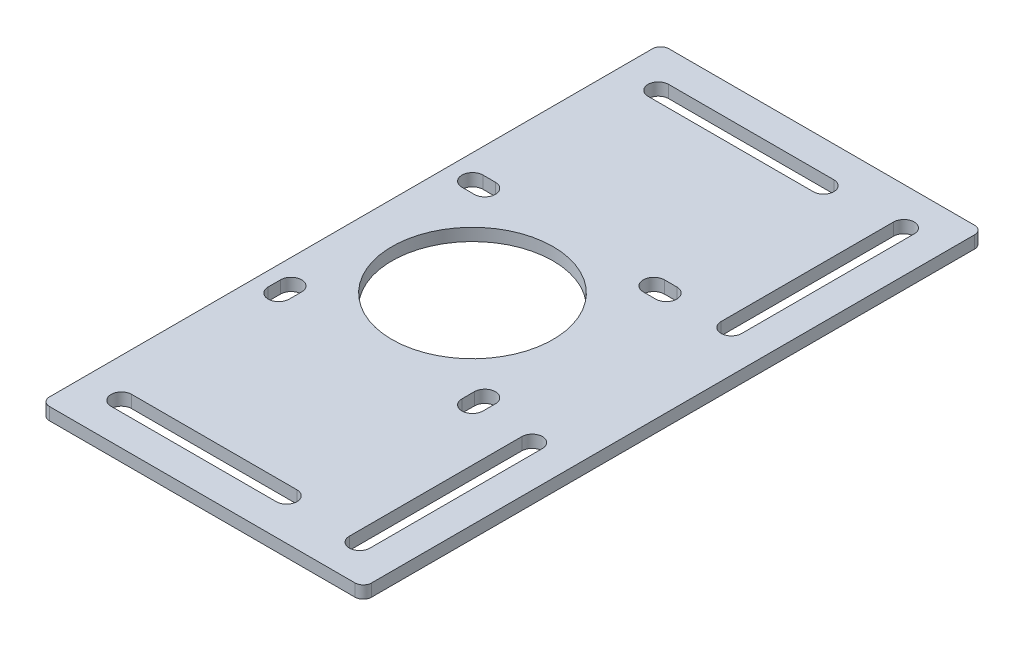
SolidWorks part; units mm, degrees
material "5052-O, Rod (SS)"
ref_plane "Front Plane" through (0, 0, 0) normal (0, 0, 1) x (1, 0, 0)
ref_plane "Top Plane" through (0, 0, 0) normal (0, 1, 0) x (1, 0, 0)
ref_plane "Right Plane" through (0, 0, 0) normal (1, 0, 0) x (0, 0, -1)
sketch "Sketch1" plane through (0, 0, 0) normal (0, 1, 0) x (1, 0, 0)
  line L0 (-39, 0) -> (39, 0) construction
  line L1 (-37, 75) -> (37, 75)
  line L2 (-39, 73) -> (-39, -73)
  line L3 (-37, -75) -> (37, -75)
  line L4 (39, 73) -> (39, -73)
  line L5 (-39, 75) -> (39, -75) construction
  line L6 (-39, -75) -> (39, 75) construction
  line L7 (29, 65.8767) -> (29, 24.1233) construction
  line L12 (-37.77, 28.2) -> (18.63, 28.2) construction
  line L14 (-37.77, 28.2) -> (-37.77, -28.2) construction
  line L15 (-37.77, -28.2) -> (18.63, -28.2) construction
  line L16 (18.63, 28.2) -> (18.63, -28.2) construction
  line L17 (-37.77, 28.2) -> (18.63, -28.2) construction
  line L18 (-37.77, -28.2) -> (18.63, 28.2) construction
  line L19 (31.5, 65.8767) -> (31.5, 24.1233)
  line L20 (26.5, 65.8767) -> (26.5, 24.1233)
  line L21 (29, -65.8767) -> (29, -24.1233) construction
  line L22 (31.5, -65.8767) -> (31.5, -24.1233)
  line L23 (26.5, -65.8767) -> (26.5, -24.1233)
  line L24 (-29.57, 65) -> (10.43, 65) construction
  line L25 (-29.57, 67.5) -> (10.43, 67.5)
  line L26 (-29.57, 62.5) -> (10.43, 62.5)
  line L27 (0, 75) -> (0, -75) construction
  line L28 (-29.57, -65) -> (10.43, -65) construction
  line L29 (-29.57, -67.5) -> (10.43, -67.5)
  line L30 (-29.57, -62.5) -> (10.43, -62.5)
  line L31 (-33.0283, 23.4583) -> (-30.0283, 23.4583) construction
  line L32 (-33.0283, 26.0083) -> (-30.0283, 26.0083)
  line L33 (-33.0283, 20.9083) -> (-30.0283, 20.9083)
  line L34 (-9.57, 28.2) -> (-9.57, -28.2) construction
  line L35 (13.8883, 23.4583) -> (10.8883, 23.4583) construction
  line L36 (13.8883, 26.0083) -> (10.8883, 26.0083)
  line L37 (13.8883, 20.9083) -> (10.8883, 20.9083)
  line L38 (-33.0283, -23.4583) -> (-33.0283, -20.4583) construction
  line L39 (-35.5783, -23.4583) -> (-35.5783, -20.4583)
  line L40 (-30.4783, -23.4583) -> (-30.4783, -20.4583)
  line L41 (13.8883, -23.4583) -> (13.8883, -20.4583) construction
  line L42 (16.4383, -23.4583) -> (16.4383, -20.4583)
  line L43 (11.3383, -23.4583) -> (11.3383, -20.4583)
  arc A5 (31.5, 65.8767) -> (26.5, 65.8767) centre (29, 65.8767) ccw
  arc A6 (26.5, 24.1233) -> (31.5, 24.1233) centre (29, 24.1233) ccw
  arc A7 (31.5, -65.8767) -> (26.5, -65.8767) centre (29, -65.8767) cw
  arc A8 (26.5, -24.1233) -> (31.5, -24.1233) centre (29, -24.1233) cw
  circle A9 centre (-9.57, 0) radius 19.5
  arc A14 (-29.57, 67.5) -> (-29.57, 62.5) centre (-29.57, 65) ccw
  arc A15 (10.43, 62.5) -> (10.43, 67.5) centre (10.43, 65) ccw
  arc A16 (-29.57, -67.5) -> (-29.57, -62.5) centre (-29.57, -65) cw
  arc A17 (10.43, -62.5) -> (10.43, -67.5) centre (10.43, -65) cw
  arc A18 (-39, -73) -> (-37, -75) centre (-37, -73) ccw
  arc A19 (37, -75) -> (39, -73) centre (37, -73) ccw
  arc A20 (37, 75) -> (39, 73) centre (37, 73) cw
  arc A21 (-37, 75) -> (-39, 73) centre (-37, 73) ccw
  arc A24 (-33.0283, 26.0083) -> (-33.0283, 20.9083) centre (-33.0283, 23.4583) ccw
  arc A25 (-30.0283, 20.9083) -> (-30.0283, 26.0083) centre (-30.0283, 23.4583) ccw
  arc A26 (13.8883, 26.0083) -> (13.8883, 20.9083) centre (13.8883, 23.4583) cw
  arc A27 (10.8883, 20.9083) -> (10.8883, 26.0083) centre (10.8883, 23.4583) cw
  arc A28 (-35.5783, -23.4583) -> (-30.4783, -23.4583) centre (-33.0283, -23.4583) ccw
  arc A29 (-30.4783, -20.4583) -> (-35.5783, -20.4583) centre (-33.0283, -20.4583) ccw
  arc A30 (16.4383, -23.4583) -> (11.3383, -23.4583) centre (13.8883, -23.4583) cw
  arc A31 (11.3383, -20.4583) -> (16.4383, -20.4583) centre (13.8883, -20.4583) cw
  point P0 (0, 0)
  point P8 (-9.57, 0)
  point P15 (29, 45)
  point P20 (-33.0283, 23.4583)
  point P24 (29, -45)
  point P33 (-9.57, 65)
  point P35 (-31.5283, 23.4583)
  point P40 (-9.57, 0)
  point P50 (-9.57, -65)
  point P72 (12.3883, 23.4583)
  point P79 (-33.0283, -23.4583)
  point P82 (-33.0283, -21.9583)
  point P89 (13.8883, -21.9583)
  dimension "D3" = 56.4
  dimension "D6" = 2.5
  dimension "D10" = 39
  dimension "D11" = 33.175
  dimension "D14" = 2.5
  dimension "D18" = 2
  dimension "D16" = 2.55
  dimension "D21" = 2.55
  dimension "D1" = 78
  dimension "D2" = 150
  dimension "D4" = 56.4
  dimension "D5" = 48.57
  dimension "D7" = 10
  dimension "D9" = 45
  dimension "D8" = 41.7534
  dimension "D12" = 3
  dimension "D13" = 40
  dimension "D15" = 10
  dimension "D17" = 33.175
  dimension "D19" = 9.57
  dimension "D20" = 3
extrude "Boss-Extrude1" add sketch "Sketch1" along normal blind 3
